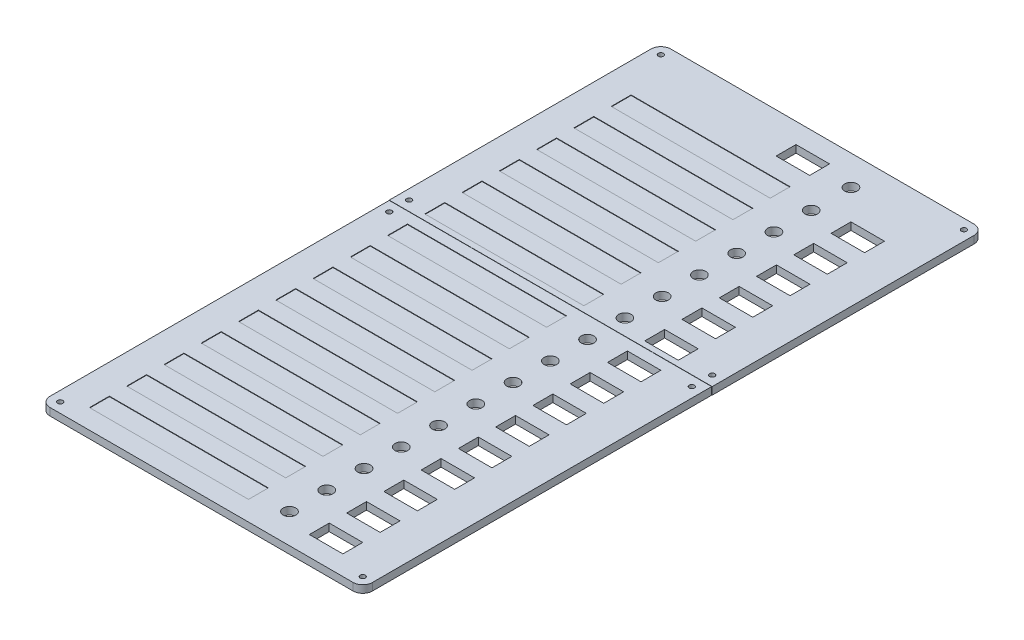
SolidWorks part; units mm, degrees
ref_plane "Ebene vorne" through (0, 0, 0) normal (0, 0, 1) x (1, 0, 0)
ref_plane "Ebene oben" through (0, 0, 0) normal (0, 1, 0) x (1, 0, 0)
ref_plane "Ebene rechts" through (0, 0, 0) normal (1, 0, 0) x (0, 0, -1)
sketch "Skizze1" plane through (0, 0, 0) normal (0, 1, 0) x (1, 0, 0)
  line L5 (-65, -125) -> (65, -125)
  line L6 (-65, -125) -> (-65, 125)
  line L11 (-65, 125) -> (65, 125)
  line L12 (65, -125) -> (65, 125)
  line L13 (-65, -125) -> (65, 125) construction
  line L14 (-65, 125) -> (65, -125) construction
  point P0 (0, 0)
  dimension "D1" = 130
  dimension "D2" = 250
extrude "Aufsatz-Linear austragen1" add sketch "Skizze1" along normal blind 3
fillet "Verrundung1" radius 4 4 edges at (-65, 1.5, 125) (65, 1.5, 125) (65, 1.5, -125) (-65, 1.5, -125)
sketch "Skizze2" plane through (0, 3, 0) normal (0, 1, 0) x (1, 0, 0)
  line L0 (-65, 15.6556) -> (65, 15.6556)
  line L1 (-65, 121) -> (-65, -121) construction
  line L2 (65, -121) -> (65, 121) construction
  line L7 (-65, 121) -> (-65, -121)
  line L8 (-61, -125) -> (61, -125)
  line L9 (65, -121) -> (65, 121)
  line L10 (61, 125) -> (-61, 125)
  line L11 (-65, 15.6556) -> (-65, -121)
  line L12 (-61, -125) -> (61, -125)
  line L13 (65, -121) -> (65, 15.6556)
  arc A4 (-65, -121) -> (-61, -125) centre (-61, -121) ccw
  arc A5 (61, -125) -> (65, -121) centre (61, -121) ccw
  arc A6 (65, 121) -> (61, 125) centre (61, 121) ccw
  arc A7 (-61, 125) -> (-65, 121) centre (-61, 121) ccw
  arc A8 (-65, -121) -> (-61, -125) centre (-61, -121) ccw
  arc A9 (61, -125) -> (65, -121) centre (61, -121) ccw
  point P6 (0, 0)
  dimension "D1" = 0
extrude "Schnitt-Linear-Austragen-Dünn1" cut sketch "Skizze2" against normal blind 3 thin
hole_wizard "Ø2.1 (2.1) Durchmesser Bohrung1" positions "Skizze3" profile "Skizze4" hole size "Ø2.1" standard "DIN"
sketch "Skizze3" plane through (0, 3, 0) normal (0, 1, 0) x (1, 0, 0)
  line L0 (-65, 121) -> (-65, 15.6556) construction
  line L1 (61, 125) -> (-61, 125) construction
  line L2 (65, 15.6556) -> (65, 121) construction
  line L3 (64.9, -121) -> (64.9, 15.5556) construction
  line L4 (65, 15.6556) -> (-65, 15.6556) construction
  line L5 (64.9, 15.5556) -> (-64.9, 15.5556) construction
  line L6 (-64.9, 15.5556) -> (-64.9, -121) construction
  line L7 (-61, -124.9) -> (61, -124.9) construction
  point P0 (-61, 121)
  point P2 (61, 121)
  point P4 (61, 19.6556)
  point P6 (60.9, 11.5556)
  point P8 (-61, 19.6556)
  point P10 (-60.9, 11.5556)
  point P12 (-60.9, -120.9)
  point P14 (60.9, -120.9)
  point P38 (-60.9, 11.1532)
  point P39 (0, 0)
  dimension "D1" = 4
  dimension "D2" = 4
  dimension "D3" = 4
  dimension "D4" = 4
  dimension "D5" = 4
  dimension "D6" = 4
  dimension "D7" = 4
  dimension "D8" = 4
  dimension "D9" = 4
  dimension "D10" = 4
  dimension "D11" = 4
  dimension "D12" = 4
  dimension "D13" = 4
  dimension "D14" = 4
  dimension "D15" = 4
  dimension "D16" = 4
sketch "Skizze4" plane through (-61, 3, -121) normal (1, 0, 0) x (0, 0, 1)
  line L0 (0, 0) -> (0, 3.6309)
  line L1 (0, 3.6309) -> (1.05, 3)
  line L2 (1.05, 3) -> (1.05, 0)
  line L5 (1.05, 0) -> (0, 0)
  line L10 (0, 3.6309) -> (-1.05, 3) construction
  line L11 (0, -6.35) -> (0, 107.95) construction
  dimension "Bohrerdurchmesser" = 2.1
  dimension "Bohrungstiefe" = 3
  dimension "Spitzenwinkel" = 118
sketch "Skizze5" plane through (0, 3, 0) normal (0, 1, 0) x (1, 0, 0)
  line L0 (65, 15.6556) -> (65, 121) construction
  line L1 (49, 101) -> (35.5, 101)
  line L2 (49, 101) -> (49, 93)
  line L3 (49, 93) -> (35.5, 93)
  line L4 (35.5, 101) -> (35.5, 93)
  line L5 (49, 101) -> (35.5, 93) construction
  line L6 (49, 93) -> (35.5, 101) construction
  line L7 (61, 125) -> (-61, 125) construction
  line L8 (49, 86) -> (35.5, 78) construction
  line L9 (49, 78) -> (35.5, 78)
  line L10 (35.5, 86) -> (35.5, 78)
  line L11 (49, 78) -> (35.5, 86) construction
  line L12 (49, 86) -> (49, 78)
  line L13 (49, 86) -> (35.5, 86)
  line L14 (49, 71) -> (35.5, 63) construction
  line L15 (49, 63) -> (35.5, 63)
  line L16 (35.5, 71) -> (35.5, 63)
  line L17 (49, 63) -> (35.5, 71) construction
  line L18 (49, 71) -> (49, 63)
  line L19 (49, 71) -> (35.5, 71)
  line L20 (49, 56) -> (35.5, 48) construction
  line L21 (49, 48) -> (35.5, 48)
  line L22 (35.5, 56) -> (35.5, 48)
  line L23 (49, 48) -> (35.5, 56) construction
  line L24 (49, 56) -> (49, 48)
  line L25 (49, 56) -> (35.5, 56)
  line L26 (49, 41) -> (35.5, 33) construction
  line L27 (49, 33) -> (35.5, 33)
  line L28 (35.5, 41) -> (35.5, 33)
  line L29 (49, 33) -> (35.5, 41) construction
  line L30 (49, 41) -> (49, 33)
  line L31 (49, 41) -> (35.5, 41)
  line L32 (49, 26) -> (35.5, 18) construction
  line L33 (49, 18) -> (35.5, 18)
  line L34 (35.5, 26) -> (35.5, 18)
  line L35 (49, 18) -> (35.5, 26) construction
  line L36 (49, 26) -> (49, 18)
  line L37 (49, 26) -> (35.5, 26)
  line L38 (49, 11) -> (35.5, 3) construction
  line L39 (49, 3) -> (35.5, 3)
  line L40 (35.5, 11) -> (35.5, 3)
  line L41 (49, 3) -> (35.5, 11) construction
  line L42 (49, 11) -> (49, 3)
  line L43 (49, 11) -> (35.5, 11)
  line L44 (49, -4) -> (35.5, -12) construction
  line L45 (49, -12) -> (35.5, -12)
  line L46 (35.5, -4) -> (35.5, -12)
  line L47 (49, -12) -> (35.5, -4) construction
  line L48 (49, -4) -> (49, -12)
  line L49 (49, -4) -> (35.5, -4)
  line L50 (49, -19) -> (35.5, -27) construction
  line L51 (49, -27) -> (35.5, -27)
  line L52 (35.5, -19) -> (35.5, -27)
  line L53 (49, -27) -> (35.5, -19) construction
  line L54 (49, -19) -> (49, -27)
  line L55 (49, -19) -> (35.5, -19)
  line L56 (49, -34) -> (35.5, -42) construction
  line L57 (49, -42) -> (35.5, -42)
  line L58 (35.5, -34) -> (35.5, -42)
  line L59 (49, -42) -> (35.5, -34) construction
  line L60 (49, -34) -> (49, -42)
  line L61 (49, -34) -> (35.5, -34)
  line L62 (49, -49) -> (35.5, -57) construction
  line L63 (49, -57) -> (35.5, -57)
  line L64 (35.5, -49) -> (35.5, -57)
  line L65 (49, -57) -> (35.5, -49) construction
  line L66 (49, -49) -> (49, -57)
  line L67 (49, -49) -> (35.5, -49)
  line L68 (49, -64) -> (35.5, -72) construction
  line L69 (49, -72) -> (35.5, -72)
  line L70 (35.5, -64) -> (35.5, -72)
  line L71 (49, -72) -> (35.5, -64) construction
  line L72 (49, -64) -> (49, -72)
  line L73 (49, -64) -> (35.5, -64)
  line L74 (49, -79) -> (35.5, -87) construction
  line L75 (49, -87) -> (35.5, -87)
  line L76 (35.5, -79) -> (35.5, -87)
  line L77 (49, -87) -> (35.5, -79) construction
  line L78 (49, -79) -> (49, -87)
  line L79 (49, -79) -> (35.5, -79)
  line L80 (49, -94) -> (35.5, -102) construction
  line L81 (49, -102) -> (35.5, -102)
  line L82 (35.5, -94) -> (35.5, -102)
  line L83 (49, -102) -> (35.5, -94) construction
  line L84 (49, -94) -> (49, -102)
  line L85 (49, -94) -> (35.5, -94)
  line L86 (49, -109) -> (35.5, -117) construction
  line L87 (49, -117) -> (35.5, -117)
  line L88 (35.5, -109) -> (35.5, -117)
  line L89 (49, -117) -> (35.5, -109) construction
  line L90 (49, -109) -> (49, -117)
  line L91 (49, -109) -> (35.5, -109)
  dimension "D1" = 8
  dimension "D2" = 13.5
  dimension "D3" = 16
  dimension "D4" = 24
  dimension "D5" = 15
extrude "Schnitt-Linear austragen3" cut sketch "Skizze5" against normal blind 3
hole_wizard "Ø5.05 (5.05) Durchmesser Bohrung1" positions "Skizze6" profile "Skizze7" hole size "Ø5.05" standard "DIN"
sketch "Skizze6" plane through (0, 3, 0) normal (0, 1, 0) x (1, 0, 0)
  line L0 (35.5, 101) -> (35.5, 93) construction
  line L1 (35.5, 86) -> (35.5, 78) construction
  point P0 (23.5, 97)
  point P2 (23.5, 82)
  point P7 (35.5, 97)
  point P10 (23.5, 67)
  point P12 (23.5, 52)
  point P14 (23.5, 37)
  point P16 (23.5, 22)
  point P18 (23.5, 7)
  point P20 (23.5, -8)
  point P22 (23.5, -23)
  point P24 (23.5, -38)
  point P26 (23.5, -53)
  point P28 (23.5, -68)
  point P30 (23.5, -83)
  point P32 (23.5, -98)
  point P34 (23.5, -113)
  dimension "D1" = 12
  dimension "D2" = 12
sketch "Skizze7" plane through (23.5, 3, -97) normal (1, 0, 0) x (0, 0, 1)
  line L0 (0, 0) -> (0, 4.5172)
  line L1 (0, 4.5172) -> (2.525, 3)
  line L2 (2.525, 3) -> (2.525, 0)
  line L5 (2.525, 0) -> (0, 0)
  line L10 (0, 4.5172) -> (-2.525, 3) construction
  line L11 (0, -6.35) -> (0, 107.95) construction
  dimension "Bohrerdurchmesser" = 5.05
  dimension "Bohrungstiefe" = 3
  dimension "Spitzenwinkel" = 118
sketch "Skizze8" plane through (0, 3, 0) normal (0, 1, 0) x (1, 0, 0)
  line L0 (-65, 121) -> (-65, 15.6556) construction
  line L1 (11, 101) -> (-53, 101)
  line L2 (11, 101) -> (11, 93)
  line L3 (11, 93) -> (-53, 93)
  line L4 (-53, 101) -> (-53, 93)
  line L5 (11, 86) -> (-53, 86)
  line L6 (11, 78) -> (-53, 78)
  line L7 (-53, 86) -> (-53, 78)
  line L8 (11, 86) -> (11, 78)
  line L9 (11, 71) -> (-53, 71)
  line L10 (11, 63) -> (-53, 63)
  line L11 (-53, 71) -> (-53, 63)
  line L12 (11, 71) -> (11, 63)
  line L13 (11, 56) -> (-53, 56)
  line L14 (11, 48) -> (-53, 48)
  line L15 (-53, 56) -> (-53, 48)
  line L16 (11, 56) -> (11, 48)
  line L17 (11, 41) -> (-53, 41)
  line L18 (11, 33) -> (-53, 33)
  line L19 (-53, 41) -> (-53, 33)
  line L20 (11, 41) -> (11, 33)
  line L21 (11, 26) -> (-53, 26)
  line L22 (11, 18) -> (-53, 18)
  line L23 (-53, 26) -> (-53, 18)
  line L24 (11, 26) -> (11, 18)
  line L25 (11, 11) -> (-53, 11)
  line L26 (11, 3) -> (-53, 3)
  line L27 (-53, 11) -> (-53, 3)
  line L28 (11, 11) -> (11, 3)
  line L29 (11, -4) -> (-53, -4)
  line L30 (11, -12) -> (-53, -12)
  line L31 (-53, -4) -> (-53, -12)
  line L32 (11, -4) -> (11, -12)
  line L33 (11, -19) -> (-53, -19)
  line L34 (11, -27) -> (-53, -27)
  line L35 (-53, -19) -> (-53, -27)
  line L36 (11, -19) -> (11, -27)
  line L37 (11, -34) -> (-53, -34)
  line L38 (11, -42) -> (-53, -42)
  line L39 (-53, -34) -> (-53, -42)
  line L40 (11, -34) -> (11, -42)
  line L41 (11, -49) -> (-53, -49)
  line L42 (11, -57) -> (-53, -57)
  line L43 (-53, -49) -> (-53, -57)
  line L44 (11, -49) -> (11, -57)
  line L45 (11, -64) -> (-53, -64)
  line L46 (11, -72) -> (-53, -72)
  line L47 (-53, -64) -> (-53, -72)
  line L48 (11, -64) -> (11, -72)
  line L49 (11, -79) -> (-53, -79)
  line L50 (11, -87) -> (-53, -87)
  line L51 (-53, -79) -> (-53, -87)
  line L52 (11, -79) -> (11, -87)
  line L53 (11, -94) -> (-53, -94)
  line L54 (11, -102) -> (-53, -102)
  line L55 (-53, -94) -> (-53, -102)
  line L56 (11, -94) -> (11, -102)
  line L57 (11, -109) -> (-53, -109)
  line L58 (11, -117) -> (-53, -117)
  line L59 (-53, -109) -> (-53, -117)
  line L60 (11, -109) -> (11, -117)
  dimension "D1" = 12
  dimension "D2" = 64
  dimension "D3" = 15
extrude "Schnitt-Linear austragen4" cut sketch "Skizze8" against normal blind 0.2
hole_wizard "Ø5.05 (5.05) Durchmesser Bohrung2" positions "Skizze11" profile "Skizze10" hole size "Ø5.05" standard "DIN"
sketch "Skizze11" plane through (0, 3, 0) normal (0, 1, 0) x (1, 0, 0)
  line L1 (11, 101) -> (-53, 101) construction
  point P0 (23.5, 113)
  dimension "D1" = 12
sketch "Skizze10" plane through (23.5, 3, -113) normal (1, 0, 0) x (0, 0, 1)
  line L0 (0, 0) -> (0, 4.5172)
  line L1 (0, 4.5172) -> (2.525, 3)
  line L2 (2.525, 3) -> (2.525, 0)
  line L5 (2.525, 0) -> (0, 0)
  line L10 (0, 4.5172) -> (-2.525, 3) construction
  line L11 (0, -6.35) -> (0, 107.95) construction
  dimension "Bohrerdurchmesser" = 5.05
  dimension "Bohrungstiefe" = 3
  dimension "Spitzenwinkel" = 118
sketch "Skizze12" plane through (0, 3, 0) normal (0, 1, 0) x (1, 0, 0)
  line L1 (-2.5, 116.889) -> (11, 116.889)
  line L2 (-2.5, 116.889) -> (-2.5, 108.889)
  line L3 (-2.5, 108.889) -> (11, 108.889)
  line L4 (11, 116.889) -> (11, 108.889)
  line L5 (-2.5, 116.889) -> (11, 108.889) construction
  line L6 (-2.5, 108.889) -> (11, 116.889) construction
  point P0 (4.25, 112.889)
  dimension "D1" = 8
  dimension "D2" = 13.5
extrude "Schnitt-Linear austragen5" cut sketch "Skizze12" against normal blind 3
